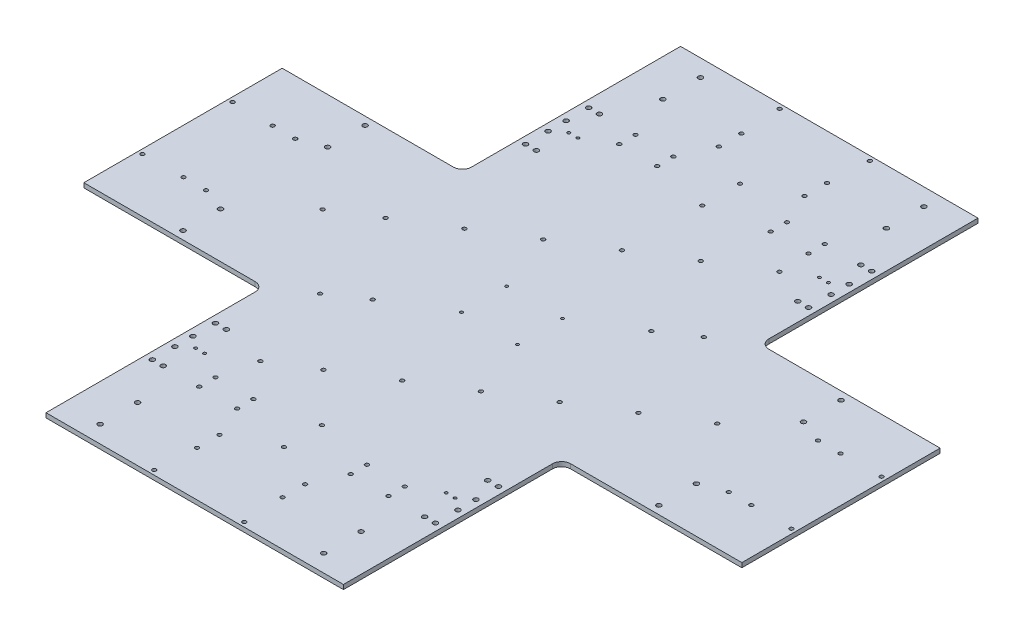
SolidWorks part; units mm, degrees
material "3.0205 (EN-AW 1200)"
ref_plane "前视基准面" through (0, 0, 0) normal (0, 0, 1) x (1, 0, 0)
ref_plane "上视基准面" through (0, 0, 0) normal (0, 1, 0) x (1, 0, 0)
ref_plane "右视基准面" through (0, 0, 0) normal (1, 0, 0) x (0, 0, -1)
other "Configuration Table"
sketch "Sketch1" plane through (0, 0, 0) normal (0, 1, 0) x (1, 0, 0)
  line L0 (165, 352) -> (-165, 352)
  line L1 (-165, 352) -> (-165, 110)
  line L2 (-165, 110) -> (-365, 110)
  line L5 (-365, 110) -> (-365, -110)
  line L6 (0, 352) -> (0, -66.8675) construction
  line L7 (-365, 0) -> (131.0517, 0) construction
  line L8 (365, 110) -> (365, -110)
  line L11 (165, 110) -> (365, 110)
  line L12 (165, 352) -> (165, 110)
  line L13 (165, -352) -> (165, -110)
  line L14 (165, -110) -> (365, -110)
  line L19 (-165, -110) -> (-365, -110)
  line L20 (-165, -352) -> (-165, -110)
  line L21 (165, -352) -> (-165, -352)
  point P21 (365, 0)
  dimension "D1" = 165
  dimension "D2" = 200
  dimension "D3" = 110
  dimension "D4" = 242
extrude "Boss-Extrude1" add sketch "Sketch1" along normal blind 5
sketch "Sketch2" plane through (0, 5, 0) normal (0, 1, 0) x (1, 0, 0)
  line L2 (365, 110) -> (165, 110) construction
  line L3 (365, -110) -> (365, 110) construction
  line L4 (-56.7455, 0) -> (47.5165, 0) construction
  line L5 (0, 54.7142) -> (0, -64.2255) construction
  line L7 (165, 352) -> (-165, 352) construction
  circle A0 centre (315, 49.5) radius 2.125
  circle A1 centre (290, 49.5) radius 2.125
  circle A7 centre (290, -49.5) radius 2.125
  circle A8 centre (315, -49.5) radius 2.125
  circle A9 centre (-315, -49.5) radius 2.125
  circle A10 centre (-290, -49.5) radius 2.125
  circle A13 centre (-290, 49.5) radius 2.125
  circle A14 centre (-315, 49.5) radius 2.125
  circle A15 centre (47.5, 302) radius 2.125
  circle A16 centre (47.5, 277) radius 2.125
  circle A17 centre (-47.5, 277) radius 2.125
  circle A18 centre (-47.5, 302) radius 2.125
  circle A19 centre (-47.5, -302) radius 2.125
  circle A20 centre (-47.5, -277) radius 2.125
  circle A21 centre (47.5, -277) radius 2.125
  circle A22 centre (47.5, -302) radius 2.125
  dimension "D1" = 60.5
  dimension "D5" = 4.25
  dimension "D7" = 4.25
  dimension "D9" = 4.25
  dimension "D10" = 4.25
  dimension "D4" = 25
  dimension "D6" = 50
  dimension "D11" = 47.5
  dimension "D12" = 50
  dimension "D13" = 25
extrude "Cut-Extrude1" cut sketch "Sketch2" against normal blind 3
sketch "Sketch4" plane through (0, 5, 0) normal (0, 1, 0) x (1, 0, 0)
  line L0 (-165, 352) -> (-165, 110) construction
  line L1 (165, 352) -> (-165, 352) construction
  line L2 (0, 46.9886) -> (0, -40.2904) construction
  line L3 (-35.103, 0) -> (92.4951, 0) construction
  line L5 (165, -352) -> (165, -110) construction
  circle A0 centre (-157, 172) radius 2.6
  circle A1 centre (-145, 172) radius 2.6
  circle A2 centre (-157, 197) radius 2.6
  circle A3 centre (-157, 217) radius 2.6
  circle A4 centre (-157, 242) radius 2.6
  circle A5 centre (-145, 242) radius 2.6
  circle A6 centre (145, 242) radius 2.6
  circle A7 centre (157, 242) radius 2.6
  circle A8 centre (157, 217) radius 2.6
  circle A9 centre (157, 197) radius 2.6
  circle A10 centre (145, 172) radius 2.6
  circle A11 centre (157, 172) radius 2.6
  circle A12 centre (157, -172) radius 2.6
  circle A13 centre (145, -172) radius 2.6
  circle A14 centre (157, -197) radius 2.6
  circle A15 centre (157, -217) radius 2.6
  circle A16 centre (157, -242) radius 2.6
  circle A17 centre (145, -242) radius 2.6
  circle A18 centre (-145, -242) radius 2.6
  circle A19 centre (-157, -242) radius 2.6
  circle A20 centre (-157, -217) radius 2.6
  circle A21 centre (-157, -197) radius 2.6
  circle A22 centre (-145, -172) radius 2.6
  circle A23 centre (-157, -172) radius 2.6
  circle A24 centre (144, -207) radius 1.6
  circle A25 centre (-144, -207) radius 1.6
  circle A26 centre (144, 207) radius 1.6
  circle A27 centre (-144, 207) radius 1.6
  circle A28 centre (134, -207) radius 1.6
  circle A29 centre (-134, -207) radius 1.6
  circle A30 centre (134, 207) radius 1.6
  circle A31 centre (-134, 207) radius 1.6
  dimension "D3" = 5.2
  dimension "D4" = 5.2
  dimension "D5" = 8
  dimension "D6" = 8
  dimension "D9" = 5.2
  dimension "D10" = 5.2
  dimension "D11" = 5.2
  dimension "D12" = 5.2
  dimension "D19" = 3.2
  dimension "D20" = 21
  dimension "D21" = 10
  dimension "D22" = 3.2
  dimension "D23" = 10
  dimension "D1" = 8
  dimension "D2" = 20
  dimension "D7" = 8
  dimension "D8" = 20
  dimension "D13" = 25
  dimension "D14" = 20
  dimension "D15" = 25
  dimension "D16" = 25
  dimension "D17" = 110
  dimension "D18" = 0
extrude "Cut-Extrude3" cut sketch "Sketch4" against normal blind 10
sketch "Sketch5" plane through (0, 5, 0) normal (0, 1, 0) x (1, 0, 0)
  line L0 (165, 352) -> (-165, 352) construction
  line L5 (-46.9195, 0) -> (66.6223, 0) construction
  line L6 (0, 59.0569) -> (0, -54.4849) construction
  line L10 (-365, 110) -> (-365, -110) construction
  line L12 (-165, 110) -> (-365, 110) construction
  line L13 (-365, -110) -> (-165, -110) construction
  circle A0 centre (-50, 347) radius 2.125
  circle A1 centre (50, 347) radius 2.125
  circle A2 centre (50, -347) radius 2.125
  circle A3 centre (-50, -347) radius 2.125
  circle A4 centre (-360, 50) radius 2.125
  circle A5 centre (-360, -50) radius 2.125
  circle A6 centre (360, -50) radius 2.125
  circle A7 centre (360, 50) radius 2.125
  dimension "D1" = 4.25
  dimension "D2" = 4.25
  dimension "D3" = 60
  dimension "D6" = 4.25
  dimension "D7" = 4.25
  dimension "5" = 5
  dimension "D4" = 50
  dimension "D5" = 50
  dimension "D8" = 60
  dimension "D9" = 5
  dimension "D10" = 5
extrude "Cut-Extrude4" cut sketch "Sketch5" against normal blind 10
fillet "Fillet1" radius 10 4 edges at (-165, 2.5, -110) (-165, 2.5, 110) (165, 2.5, 110) (165, 2.5, -110)
sketch "Sketch6" plane through (0, 5, 0) normal (0, 1, 0) x (1, 0, 0)
  line L0 (165, 352) -> (-165, 352) construction
  line L2 (165, 120) -> (165, 352) construction
  line L3 (-64.416, 0) -> (103.2752, 0) construction
  line L4 (0, 86.0771) -> (0, -73.7041) construction
  line L5 (365, 110) -> (175, 110) construction
  line L6 (365, -110) -> (365, 110) construction
  circle A0 centre (124, 333) radius 2.6
  circle A1 centre (124, 291.4) radius 2.6
  circle A2 centre (124, -291.4) radius 2.6
  circle A3 centre (124, -333) radius 2.6
  circle A4 centre (-124, -333) radius 2.6
  circle A5 centre (-124, -291.4) radius 2.6
  circle A6 centre (-124, 291.4) radius 2.6
  circle A7 centre (-124, 333) radius 2.6
  circle A8 centre (264, 101) radius 2.6
  circle A9 centre (264, 59.4) radius 2.6
  circle A10 centre (264, -59.4) radius 2.6
  circle A11 centre (264, -101) radius 2.6
  circle A12 centre (-264, -101) radius 2.6
  circle A13 centre (-264, -59.4) radius 2.6
  circle A14 centre (-264, 59.4) radius 2.6
  circle A15 centre (-264, 101) radius 2.6
  dimension "D1" = 5.2
  dimension "D2" = 5.2
  dimension "D6" = 5.2
  dimension "D7" = 5.2
  dimension "D3" = 19
  dimension "D4" = 41
  dimension "D5" = 41.6
  dimension "D8" = 9
  dimension "D9" = 41.6
  dimension "D10" = 101
extrude "Cut-Extrude5" cut sketch "Sketch6" against normal blind 10
sketch "Sketch7" plane through (0, 5, 0) normal (0, 1, 0) x (1, 0, 0)
  line L0 (197.463, 121.9013) -> (-168.3949, -103.9565) construction
  line L1 (180, 235.6925) -> (-379.973, -110) construction
  line L2 (144.6063, 226.5583) -> (333.7962, -79.9026) construction
  line L3 (-55.682, 90.1971) -> (55.682, -90.1971) construction
  line L4 (-167.9289, -112.9289) -> (167.9289, 112.9289) construction
  circle A0 centre (-55.682, 90.1971) radius 2.125
  circle A1 centre (-1.6489, 123.5538) radius 2.125
  circle A2 centre (52.3842, 156.9105) radius 2.125
  circle A3 centre (106.4174, 190.2672) radius 2.125
  circle A4 centre (-109.7152, 56.8404) radius 2.125
  circle A5 centre (-163.7483, 23.4837) radius 2.125
  circle A6 centre (-206.9749, -3.2017) radius 2.125
  circle A7 centre (-95.6108, -183.5958) radius 2.125
  circle A8 centre (-52.3842, -156.9105) radius 2.125
  circle A9 centre (1.6489, -123.5538) radius 2.125
  circle A10 centre (217.7815, 9.873) radius 2.125
  circle A11 centre (163.7483, -23.4837) radius 2.125
  circle A12 centre (109.7152, -56.8404) radius 2.125
  circle A13 centre (55.682, -90.1971) radius 2.125
  arc A14 (165, 120) -> (175, 110) centre (175, 120) ccw construction
  arc A15 (-165, -120) -> (-175, -110) centre (-175, -120) ccw construction
  point P35 (0, 0)
  point P36 (167.9289, 112.9289)
  point P37 (-167.9289, -112.9289)
  dimension "D1" = 4.25
  dimension "D2" = 4.25
  dimension "D3" = 4.25
  dimension "4.25" = 4.25
  dimension "D5" = 4.25
  dimension "D6" = 4.25
  dimension "D7" = 4.25
  dimension "D8" = 63.5
  dimension "D9" = 63.5
  dimension "D10" = 50.8
  dimension "D11" = 63.5
  dimension "D12" = 63.5
  dimension "D13" = 63.5
  dimension "D14" = 0
  dimension "D15" = 0
  dimension "D16" = 106
extrude "Cut-Extrude6" cut sketch "Sketch7" against normal blind 10
sketch "Sketch8" plane through (0, 5, 0) normal (0, 1, 0) x (1, 0, 0)
  line L0 (167.9289, 112.9289) -> (-167.9289, -112.9289) construction
  line L1 (81.1937, 116.467) -> (145.4556, 20.9075) construction
  line L2 (-135.7714, -35.3081) -> (-80.5576, -117.413) construction
  line L3 (0, 77.1364) -> (0, -65.7088) construction
  line L4 (-60.3124, 0) -> (69.2005, 0) construction
  line L5 (165, 352) -> (-165, 352) construction
  arc A0 (165, 120) -> (175, 110) centre (175, 120) ccw construction
  arc A1 (-165, -120) -> (-175, -110) centre (-175, -120) ccw construction
  circle A2 centre (-127.2679, -85.5852) radius 2.1
  circle A3 centre (-92.4156, -62.1477) radius 2.1
  circle A4 centre (92.4156, 62.1477) radius 2.1
  circle A5 centre (127.2679, 85.5852) radius 2.1
  circle A6 centre (0, 253) radius 2.1
  circle A7 centre (0, 211) radius 2.1
  circle A8 centre (0, -211) radius 2.1
  circle A9 centre (0, -253) radius 2.1
  dimension "D3" = 4.2
  dimension "D4" = 4.2
  dimension "D5" = 4.2
  dimension "D6" = 4.2
  dimension "D8" = 21
  dimension "D11" = 4.2
  dimension "D12" = 4.2
  dimension "D1" = 70
  dimension "D2" = 70
  dimension "D7" = 21
  dimension "D9" = 21
  dimension "D10" = 21
  dimension "D13" = 99
  dimension "D14" = 42
extrude "Cut-Extrude7" cut sketch "Sketch8" against normal blind 10
sketch "Sketch9" plane through (0, 5, 0) normal (0, 1, 0) x (1, 0, 0)
  line L0 (0, 50.376) -> (0, -37.6511) construction
  line L1 (-100.5221, 0) -> (79.2832, 0) construction
  circle A0 centre (-31, 25) radius 1.575
  circle A1 centre (-31, -25) radius 1.575
  circle A2 centre (31, -25) radius 1.575
  circle A3 centre (31, 25) radius 1.575
  dimension "D1" = 3.15
  dimension "D2" = 31
  dimension "D3" = 25
extrude "Cut-Extrude8" cut sketch "Sketch9" against normal blind 10
sketch "Sketch11" plane through (0, 5, 0) normal (0, 1, 0) x (1, 0, 0)
  line L0 (0, 181.8895) -> (0, -221.8861) construction
  line L1 (-154.2728, 0) -> (170.1444, 0) construction
  line L2 (165, 120) -> (165, 352) construction
  line L3 (165, 352) -> (-165, 352) construction
  circle A0 centre (63, 242) radius 2.125
  circle A1 centre (63, 224) radius 2.125
  circle A2 centre (105, 242) radius 2.125
  circle A3 centre (105, 224) radius 2.125
  circle A4 centre (-105, 224) radius 2.125
  circle A5 centre (-105, 242) radius 2.125
  circle A6 centre (-63, 224) radius 2.125
  circle A7 centre (-63, 242) radius 2.125
  circle A8 centre (-63, -242) radius 2.125
  circle A9 centre (-63, -224) radius 2.125
  circle A10 centre (-105, -242) radius 2.125
  circle A11 centre (-105, -224) radius 2.125
  circle A12 centre (105, -224) radius 2.125
  circle A13 centre (105, -242) radius 2.125
  circle A14 centre (63, -224) radius 2.125
  circle A15 centre (63, -242) radius 2.125
  dimension "D1" = 4.25
  dimension "D2" = 4.25
  dimension "D5" = 4.25
  dimension "D6" = 4.25
  dimension "D3" = 18
  dimension "D4" = 42
  dimension "D7" = 60
  dimension "D8" = 110
extrude "Cut-Extrude9" cut sketch "Sketch11" against normal blind 10
